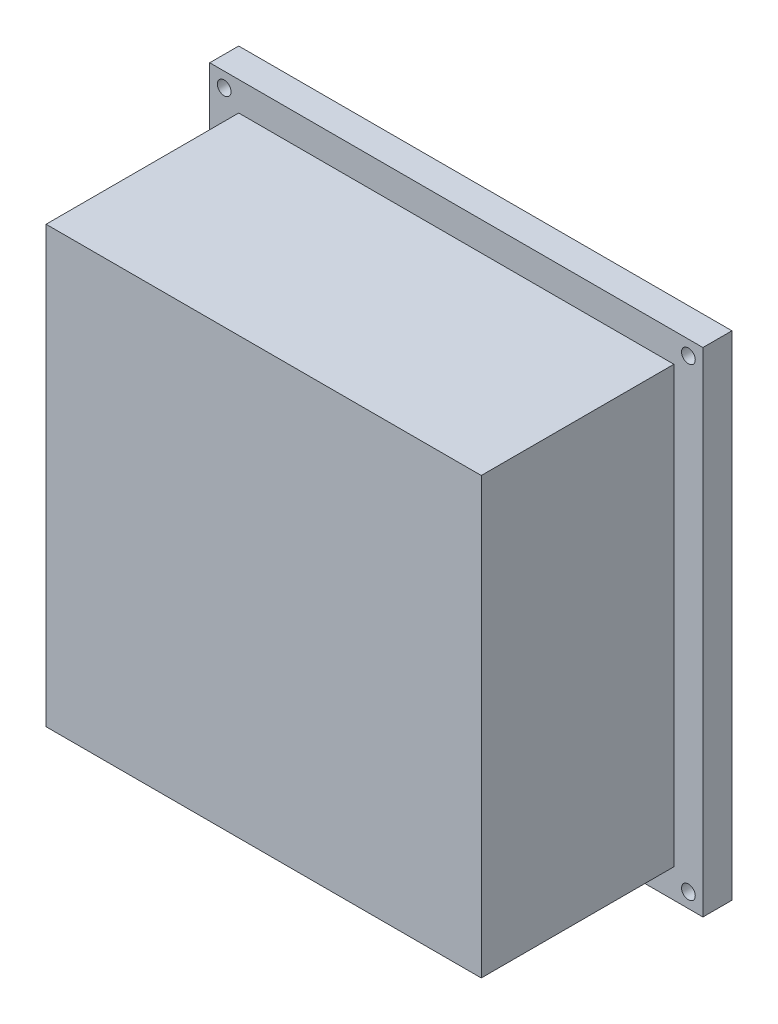
SolidWorks part; units mm, degrees
ref_plane "Front Plane" through (0, 0, 0) normal (0, 0, 1) x (1, 0, 0)
ref_plane "Top Plane" through (0, 0, 0) normal (0, 1, 0) x (1, 0, 0)
ref_plane "Right Plane" through (0, 0, 0) normal (1, 0, 0) x (0, 0, -1)
sketch "Sketch6" plane through (0, 0, 0) normal (0, 0, 1) x (1, 0, 0)
  line L1 (-53.975, 53.975) -> (53.975, 53.975)
  line L2 (-53.975, 53.975) -> (-53.975, -53.975)
  line L3 (-53.975, -53.975) -> (53.975, -53.975)
  line L4 (53.975, 53.975) -> (53.975, -53.975)
  line L5 (-53.975, 53.975) -> (53.975, -53.975) construction
  line L6 (-53.975, -53.975) -> (53.975, 53.975) construction
  line L11 (-47.625, 47.625) -> (47.625, -47.625) construction
  line L12 (0, -67.3519) -> (0, 67.3519) construction
  line L13 (-44.45, 44.45) -> (44.45, 44.45)
  line L14 (-44.45, 44.45) -> (-44.45, -44.45)
  line L15 (-44.45, -44.45) -> (44.45, -44.45)
  line L16 (44.45, 44.45) -> (44.45, -44.45)
  line L17 (-44.45, 44.45) -> (44.45, -44.45) construction
  line L18 (-44.45, -44.45) -> (44.45, 44.45) construction
  line L23 (-47.625, 47.625) -> (47.625, -47.625) construction
  line L24 (0, -67.3519) -> (0, 67.3519) construction
  line L25 (-44.45, 44.45) -> (44.45, 44.45)
  line L26 (-44.45, 44.45) -> (-44.45, -44.45)
  line L27 (-44.45, -44.45) -> (44.45, -44.45)
  line L28 (44.45, 44.45) -> (44.45, -44.45)
  line L29 (-44.45, 44.45) -> (44.45, -44.45) construction
  line L30 (-44.45, -44.45) -> (44.45, 44.45) construction
  line L31 (-47.625, 47.625) -> (47.625, 47.625)
  line L32 (-47.625, 47.625) -> (-47.625, -47.625)
  line L33 (-47.625, -47.625) -> (47.625, -47.625)
  line L34 (47.625, 47.625) -> (47.625, -47.625)
  line L35 (-47.625, 47.625) -> (47.625, -47.625) construction
  line L36 (-47.625, -47.625) -> (47.625, 47.625) construction
  circle A0 centre (-50.8, 50.8) radius 1.5
  circle A1 centre (50.8, 50.8) radius 1.5
  circle A2 centre (50.8, -50.8) radius 1.5
  circle A3 centre (-50.8, -50.8) radius 1.5
  point P0 (0, 0)
  point P5 (0, 0)
  point P18 (0, 0)
  point P23 (0, 0)
  point P24 (0, 0)
  point P25 (0, 0)
extrude "Boss-Extrude3" add sketch "Sketch6" along normal blind 42.164 contours L34 L31 L32 L33 L13 L16 L15 L14
sketch "Sketch7" plane through (0, 0, 0) normal (0, 0, 1) x (1, 0, 0)
  line L1 (-47.625, 47.625) -> (47.625, 47.625)
  line L2 (-47.625, 47.625) -> (-47.625, -47.625)
  line L3 (-47.625, -47.625) -> (47.625, -47.625)
  line L4 (47.625, 47.625) -> (47.625, -47.625)
  line L5 (-47.625, 47.625) -> (47.625, -47.625) construction
  line L6 (-47.625, -47.625) -> (47.625, 47.625) construction
  line L7 (-53.975, 53.975) -> (53.975, 53.975)
  line L8 (-53.975, 53.975) -> (-53.975, -53.975)
  line L9 (-53.975, -53.975) -> (53.975, -53.975)
  line L10 (53.975, 53.975) -> (53.975, -53.975)
  line L11 (-53.975, 53.975) -> (53.975, -53.975) construction
  line L12 (-53.975, -53.975) -> (53.975, 53.975) construction
  circle A0 centre (-50.8, 50.8) radius 1.5
  circle A1 centre (50.8, 50.8) radius 1.5
  circle A2 centre (-50.8, -50.8) radius 1.5
  circle A3 centre (50.8, -50.8) radius 1.5
  point P0 (0, 0)
  point P5 (0, 0)
extrude "Boss-Extrude4" add sketch "Sketch7" along normal blind 6.35
sketch "Sketch8" plane through (0, 0, 42.164) normal (0, 0, 1) x (1, 0, 0)
  line L0 (-47.625, -47.625) -> (47.625, -47.625) construction
  line L1 (-47.625, 47.625) -> (47.625, 47.625)
  line L2 (-47.625, 47.625) -> (-47.625, -47.625)
  line L3 (-47.625, -47.625) -> (47.625, -47.625)
  line L4 (47.625, 47.625) -> (47.625, -47.625)
  line L5 (-47.625, 47.625) -> (47.625, -47.625) construction
  line L6 (-47.625, -47.625) -> (47.625, 47.625) construction
  point P0 (0, 0)
extrude "Boss-Extrude5" add sketch "Sketch8" along normal blind 6.35
